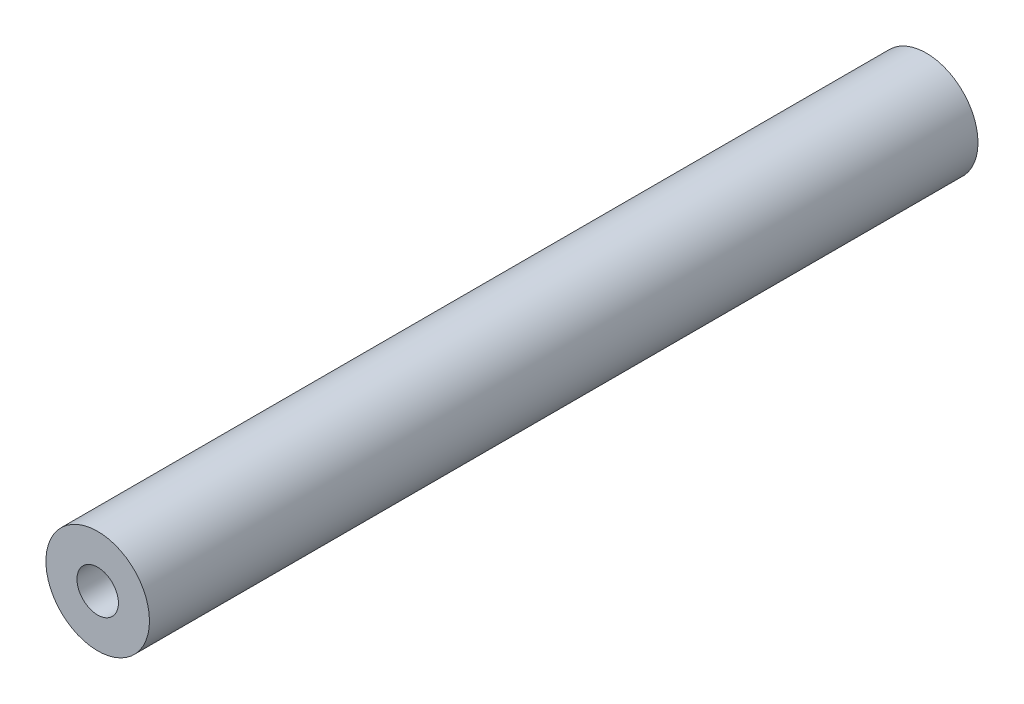
SolidWorks part; units mm, degrees
ref_plane "前视基准面" through (0, 0, 0) normal (0, 0, 1) x (1, 0, 0)
ref_plane "上视基准面" through (0, 0, 0) normal (0, 1, 0) x (1, 0, 0)
ref_plane "右视基准面" through (0, 0, 0) normal (1, 0, 0) x (0, 0, -1)
other "Configuration Table"
sketch "草图1" plane through (0, 0, 0) normal (0, 0, 1) x (1, 0, 0)
  circle A0 centre (0, 0) radius 4
  circle A1 centre (0, 0) radius 1.6
extrude "凸台-拉伸1" add sketch "草图1" along normal mid plane 64
